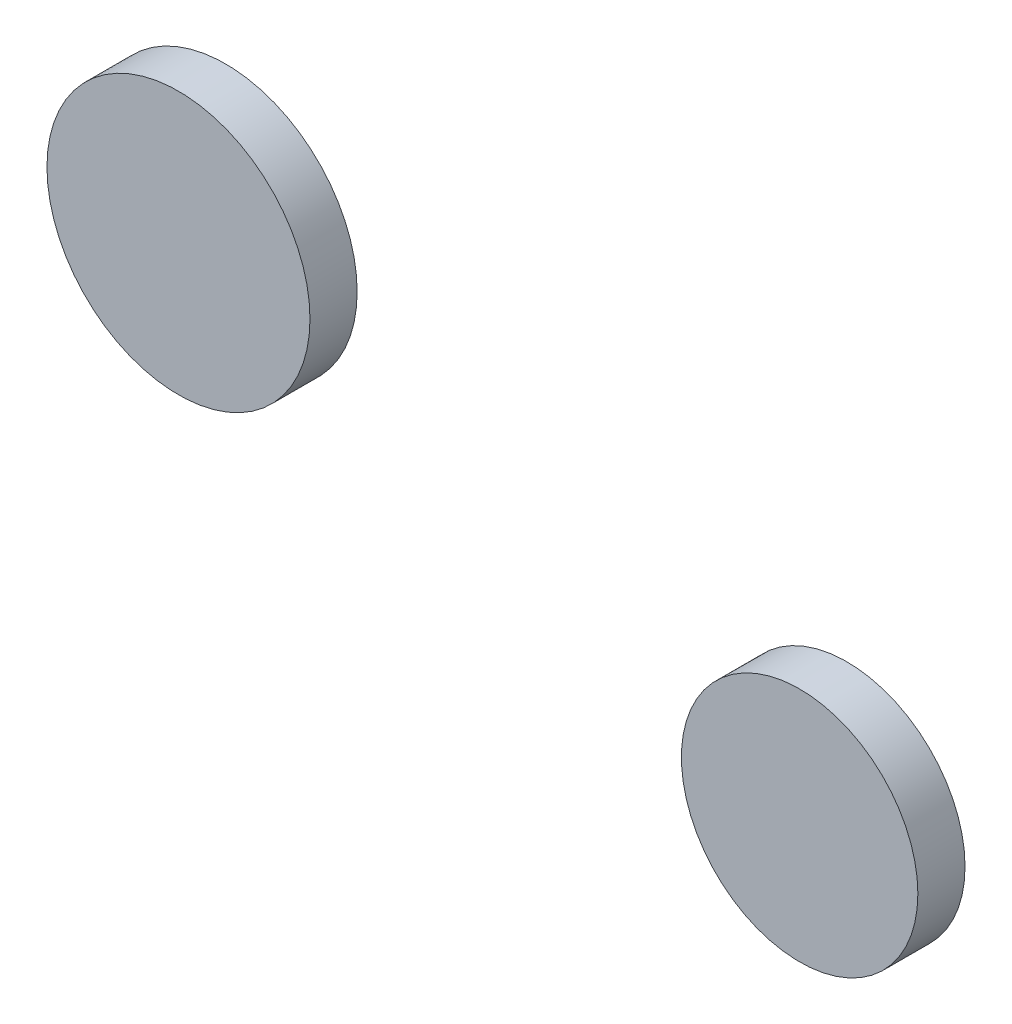
SolidWorks part; units mm, degrees
ref_plane "前视基准面" through (0, 0, 0) normal (0, 0, 1) x (1, 0, 0)
ref_plane "上视基准面" through (0, 0, 0) normal (0, 1, 0) x (1, 0, 0)
ref_plane "右视基准面" through (0, 0, 0) normal (1, 0, 0) x (0, 0, -1)
sketch "草图1" plane through (0, 0, 0) normal (0, 0, 1) x (1, 0, 0)
  circle A0 centre (-54.369, 10.847) radius 25.0687
  circle A1 centre (-186.0657, 51.9488) radius 27.883
  point P4 (0, 0)
extrude "凸台-拉伸1" add sketch "草图1" along normal blind 10
